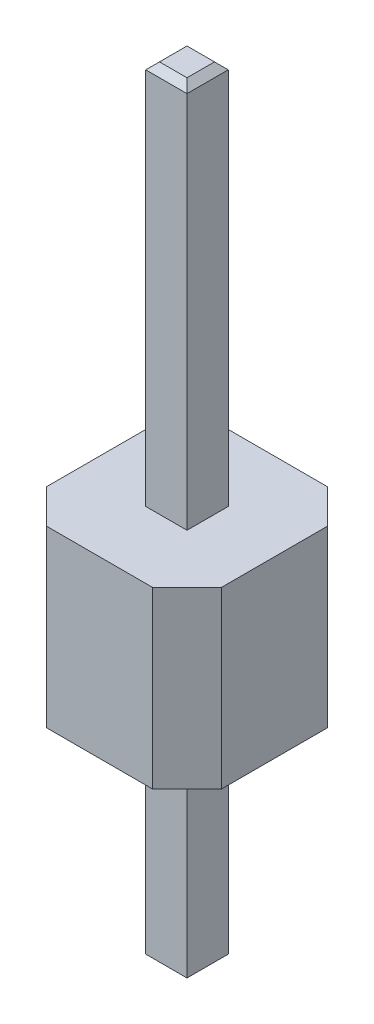
SolidWorks part; units mm, degrees
material "45"
ref_plane "前视基准面" through (0, 0, 0) normal (0, 0, 1) x (1, 0, 0)
ref_plane "上视基准面" through (0, 0, 0) normal (0, 1, 0) x (1, 0, 0)
ref_plane "右视基准面" through (0, 0, 0) normal (1, 0, 0) x (0, 0, -1)
sketch "草图1" plane through (0, 0, 0) normal (0, 1, 0) x (1, 0, 0)
  line L1 (-1.27, 1.27) -> (1.27, 1.27)
  line L2 (-1.27, 1.27) -> (-1.27, -1.27)
  line L3 (-1.27, -1.27) -> (1.27, -1.27)
  line L4 (1.27, 1.27) -> (1.27, -1.27)
  line L5 (-1.27, 1.27) -> (1.27, -1.27) construction
  line L6 (-1.27, -1.27) -> (1.27, 1.27) construction
  point P0 (0, 0)
  dimension "D1" = 2.54
  dimension "D2" = 2.54
extrude "凸台-拉伸1" add sketch "草图1" along normal blind 2.54
sketch "草图2" plane through (0, 2.54, 0) normal (0, 1, 0) x (1, 0, 0)
  line L1 (-0.3, 0.3) -> (0.3, 0.3)
  line L2 (-0.3, 0.3) -> (-0.3, -0.3)
  line L3 (-0.3, -0.3) -> (0.3, -0.3)
  line L4 (0.3, 0.3) -> (0.3, -0.3)
  line L5 (-0.3, 0.3) -> (0.3, -0.3) construction
  line L6 (-0.3, -0.3) -> (0.3, 0.3) construction
  point P0 (0, 0)
  dimension "D1" = 0.6
  dimension "D2" = 0.6
extrude "凸台-拉伸2" add sketch "草图2" along normal blind 5.6
sketch "草图3" plane through (0, 0, 0) normal (0, -1, 0) x (1, 0, 0)
  line L1 (0.3, -0.3) -> (-0.3, -0.3)
  line L2 (0.3, -0.3) -> (0.3, 0.3)
  line L3 (0.3, 0.3) -> (-0.3, 0.3)
  line L4 (-0.3, -0.3) -> (-0.3, 0.3)
  line L5 (0.3, -0.3) -> (-0.3, 0.3) construction
  line L6 (0.3, 0.3) -> (-0.3, -0.3) construction
  point P0 (0, 0)
extrude "凸台-拉伸3" add sketch "草图3" along normal blind 3.2
chamfer "倒角1" distance 0.1 angle 45 8 edges at (0, -3.2, 0.3) (0.3, -3.2, 0) (0, -3.2, -0.3) (-0.3, -3.2, 0) (0, 8.14, 0.3) (-0.3, 8.14, 0) (0, 8.14, -0.3) (0.3, 8.14, 0)
chamfer "倒角2" distance 0.5 angle 45 4 edges at (-1.27, 1.27, 1.27) (-1.27, 1.27, -1.27) (1.27, 1.27, -1.27) (1.27, 1.27, 1.27)
sketch "草图4" plane through (0, -3.2, 0) normal (0, -1, 0) x (1, 0, 0)
  circle A0 centre (0, 0) radius 0.0418
extrude "切除-拉伸1" cut sketch "草图4" against normal blind 10
